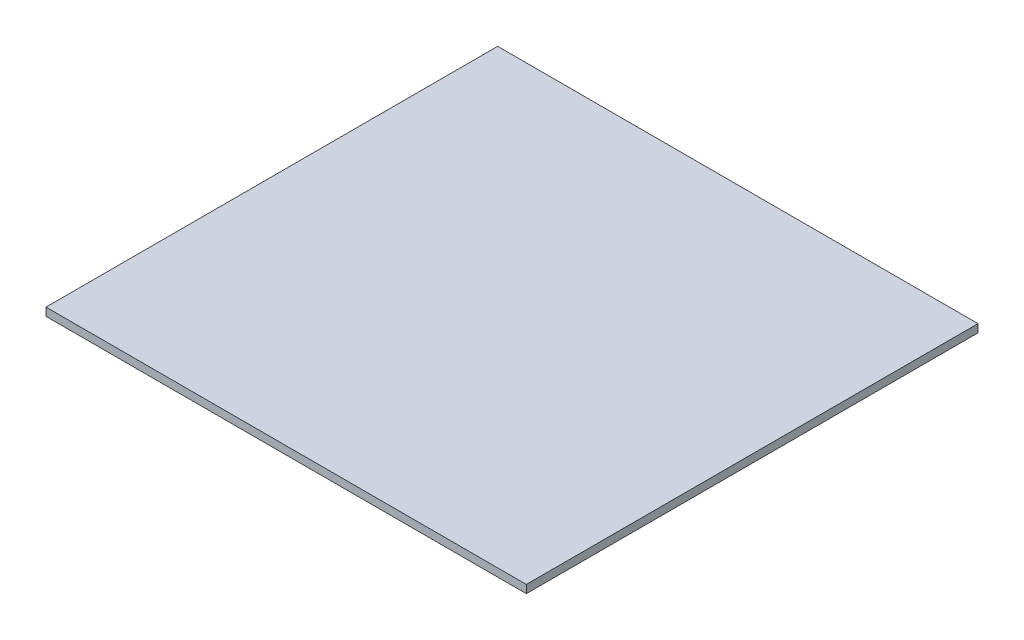
SolidWorks part; units mm, degrees
ref_plane "Front Plane" through (0, 0, 0) normal (0, 0, 1) x (1, 0, 0)
ref_plane "Top Plane" through (0, 0, 0) normal (0, 1, 0) x (1, 0, 0)
ref_plane "Right Plane" through (0, 0, 0) normal (1, 0, 0) x (0, 0, -1)
sketch "Sketch1" plane through (0, 0, 0) normal (0, 1, 0) x (1, 0, 0)
  line L0 (0, 0) -> (0, 45.085) construction
  line L1 (0, 0) -> (47.945, 0) construction
  line L3 (47.945, 45.085) -> (-47.945, 45.085)
  line L4 (47.945, 45.085) -> (47.945, -45.085)
  line L5 (47.945, -45.085) -> (-47.945, -45.085)
  line L6 (-47.945, 45.085) -> (-47.945, -45.085)
extrude "Boss-Extrude1" add sketch "Sketch1" along normal blind 1.6
